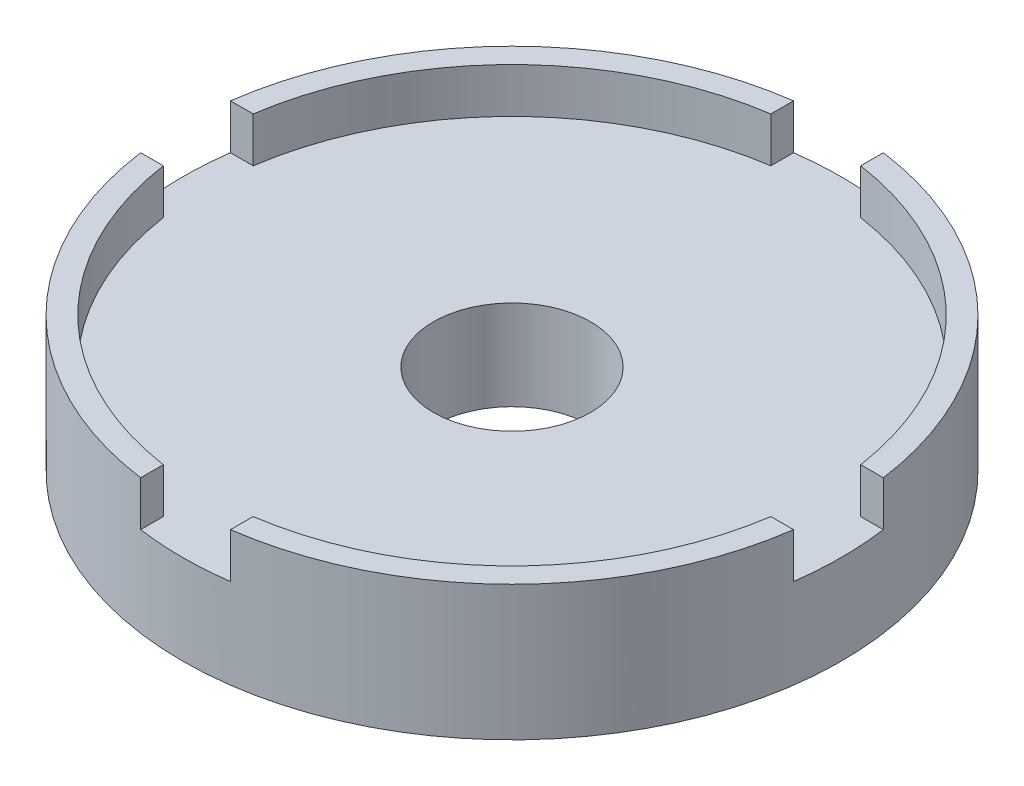
SolidWorks part; units mm, degrees
material "Delrin 2700 NC010, Low Viscosity Acetal Copolymer (SS)"
ref_plane "Front Plane" through (0, 0, 0) normal (0, 0, 1) x (1, 0, 0)
ref_plane "Top Plane" through (0, 0, 0) normal (0, 1, 0) x (1, 0, 0)
ref_plane "Right Plane" through (0, 0, 0) normal (1, 0, 0) x (0, 0, -1)
sketch "Sketch1" plane through (0, 0, 0) normal (0, 1, 0) x (1, 0, 0)
  circle A0 centre (4.0023, -4.8181) radius 17.5
  circle A1 centre (4.0023, -4.8181) radius 68.354
extrude "Boss-Extrude2" add sketch "Sketch1" along normal blind 20
sketch "Sketch2" plane through (0, 20, 0) normal (0, 1, 0) x (1, 0, 0)
  circle A0 centre (4.0023, -4.8181) radius 68.354
  circle A1 centre (4.0023, -4.8181) radius 73.354
  dimension "D1" = 5
extrude "Boss-Extrude3" add sketch "Sketch2" along normal blind 10 and the other way blind 20
sketch "Sketch3" plane through (0, 0, 0) normal (1, 0, 0) x (0, 0, -1)
  line L0 (-4.8181, 30) -> (5.1819, 30)
  line L1 (68.5359, 30) -> (-78.1721, 30) construction
  line L2 (63.5359, 30) -> (-73.1721, 30) construction
  line L4 (5.1819, 30) -> (5.1819, 20)
  line L5 (5.1819, 20) -> (-14.8181, 20)
  line L6 (-14.8181, 20) -> (-14.8181, 30)
  line L7 (-14.8181, 30) -> (-4.8181, 30)
  dimension "D1" = 10
  dimension "D2" = 10
  dimension "D3" = 20
extrude "Cut-Extrude1" cut sketch "Sketch3" against normal through all and the other way through all
sketch "Sketch5" plane through (0, 0, 0) normal (0, 0, 1) x (1, 0, 0)
  line L0 (77.3563, 20) -> (-69.3517, 20) construction
  line L1 (4.0023, 30) -> (14.0023, 30)
  line L2 (76.6715, 30) -> (-68.6669, 30) construction
  line L3 (14.0023, 30) -> (14.0023, 20)
  line L4 (14.0023, 20) -> (-5.9977, 20)
  line L5 (-5.9977, 20) -> (-5.9977, 30)
  line L6 (-5.9977, 30) -> (4.0023, 30)
  dimension "D1" = 10
  dimension "D2" = 10
  dimension "D3" = 20
extrude "Cut-Extrude2" cut sketch "Sketch5" against normal through all and the other way through all
